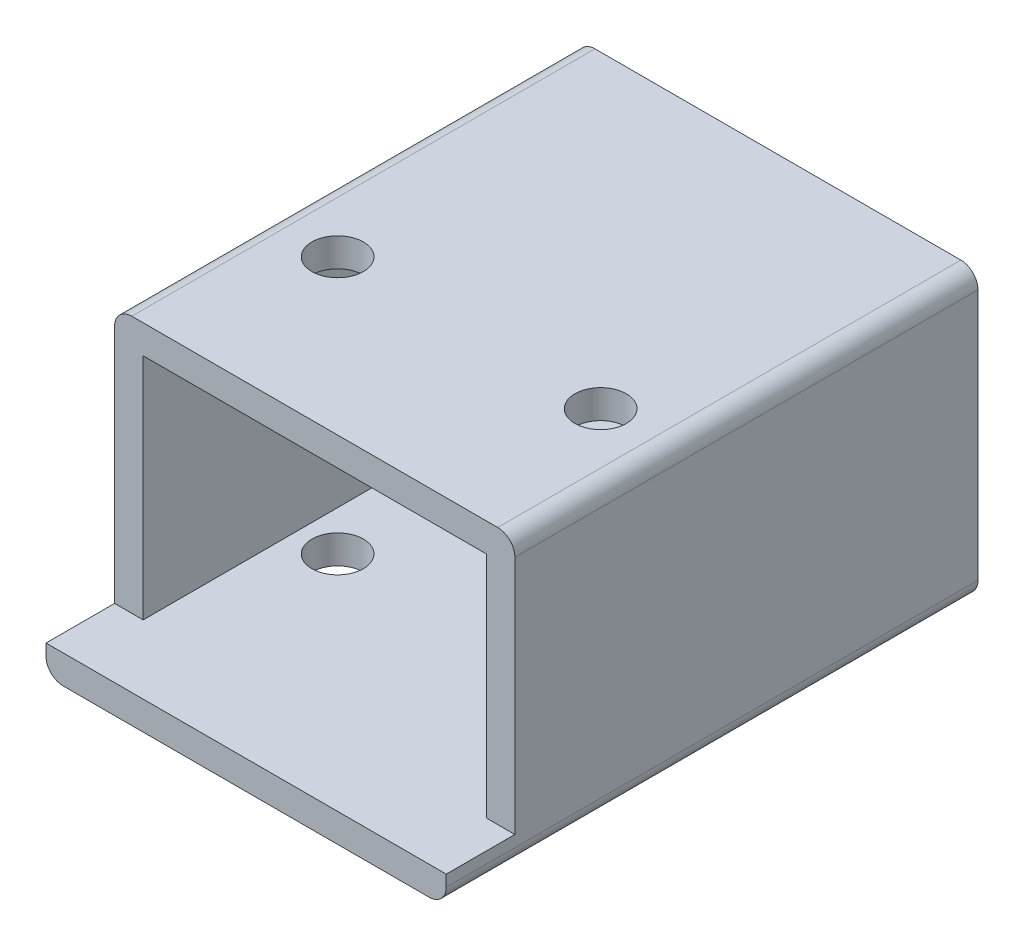
SolidWorks part; units mm, degrees
ref_plane "Front Plane" through (0, 0, 0) normal (0, 0, 1) x (1, 0, 0)
ref_plane "Top Plane" through (0, 0, 0) normal (0, 1, 0) x (1, 0, 0)
ref_plane "Right Plane" through (0, 0, 0) normal (1, 0, 0) x (0, 0, -1)
sketch "Sketch1" plane through (0, 0, 0) normal (0, 0, 1) x (1, 0, 0)
  line L1 (35, -25) -> (-35, -25)
  line L2 (35, -25) -> (35, 25)
  line L3 (35, 25) -> (-35, 25)
  line L4 (-35, -25) -> (-35, 25)
  line L5 (35, -25) -> (-35, 25) construction
  line L6 (35, 25) -> (-35, -25) construction
  point P0 (0, 0)
extrude "Boss-Extrude1" add sketch "Sketch1" along normal blind 5
sketch "Sketch2" plane through (0, 0, 5) normal (0, 0, 1) x (1, 0, 0)
  line L0 (-35, 25) -> (-35, -25) construction
  line L1 (35, -25) -> (-35, -25)
  line L2 (35, -25) -> (35, -20)
  line L3 (35, -20) -> (-35, -20)
  line L4 (-35, -25) -> (-35, -20)
  dimension "D1" = 5
extrude "Boss-Extrude2" add sketch "Sketch2" along normal blind 88
sketch "Sketch3" plane through (0, 0, 5) normal (0, 0, 1) x (1, 0, 0)
  line L6 (35, -20) -> (35, 25) construction
  line L7 (-35, 25) -> (35, 25)
  line L8 (-35, 25) -> (-35, 20)
  line L9 (-30, 20) -> (30, 20)
  line L10 (35, 25) -> (35, 20)
  line L11 (35, -20) -> (-35, -20) construction
  line L13 (-35, 20) -> (-35, -20)
  line L14 (-35, -20) -> (-30, -20)
  line L15 (-30, 20) -> (-30, -20)
  line L16 (-30, -19.8) -> (-30, -20) construction
  line L17 (30, -20) -> (30, -19.8) construction
  line L19 (35, 20) -> (35, -20)
  line L20 (35, -20) -> (30, -20)
  line L21 (30, 20) -> (30, -20)
  dimension "D1" = 5
extrude "Boss-Extrude3" add sketch "Sketch3" along normal up to surface (76 mm away)
sketch "Sketch4" plane through (0, 25, 0) normal (0, 1, 0) x (1, 0, 0)
  circle A0 centre (23, -54) radius 4.5
  circle A1 centre (-23, -54) radius 4.5
  dimension "D1" = 9
  dimension "D2" = 9
extrude "Cut-Extrude1" cut sketch "Sketch4" against normal blind 56
fillet "Fillet1" radius 3 4 edges at (35, -25, 46.5) (35, 25, 40.5) (-35, 25, 40.5) (-35, -25, 46.5)
hole_wizard "CBORE for M4 Hex Head Cap Screw1" positions "Sketch8" profile "Sketch7" counterbore size "M4" standard "ISO"
sketch "Sketch8" plane through (0, 0, 5) normal (0, 0, 1) x (1, 0, 0)
  line L0 (0, 0) -> (-49.8655, 0) construction
  line L2 (0, 0) -> (0, 50.5153) construction
  point P10 (-19, 11)
  point P12 (19, 11)
  point P13 (19, -11)
  point P14 (-19, -11)
  dimension "D1" = 11
  dimension "D2" = 19
sketch "Sketch7" plane through (-19, -11, 5) normal (1, 0, 0) x (0, -1, 0)
  line L0 (0, 0) -> (0, 12.4)
  line L1 (0, 12.4) -> (2.25, 11.0481)
  line L2 (2.25, 11.0481) -> (2.25, 2.8)
  line L3 (2.25, 2.8) -> (5.5415, 2.8)
  line L5 (5.5415, 2.8) -> (5.5415, 0.025)
  line L6 (5.5415, 0.025) -> (5.5665, 0)
  line L7 (5.5665, 0) -> (0, 0)
  line L8 (-5.5415, 0.025) -> (-5.5665, 0) construction
  line L10 (0, 12.4) -> (-2.25, 11.0481) construction
  line L11 (0, -6.35) -> (0, 107.95) construction
  dimension "Hole Dia." = 4.5
  dimension "Hole Depth" = 12.4
  dimension "C'Bore Dia." = 11.083
  dimension "C'Bore Depth" = 2.8
  dimension "Near C'Sink Dia." = 11.133
  dimension "Near C'Sink Angle" = 90
  dimension "Drill Angle" = 118
